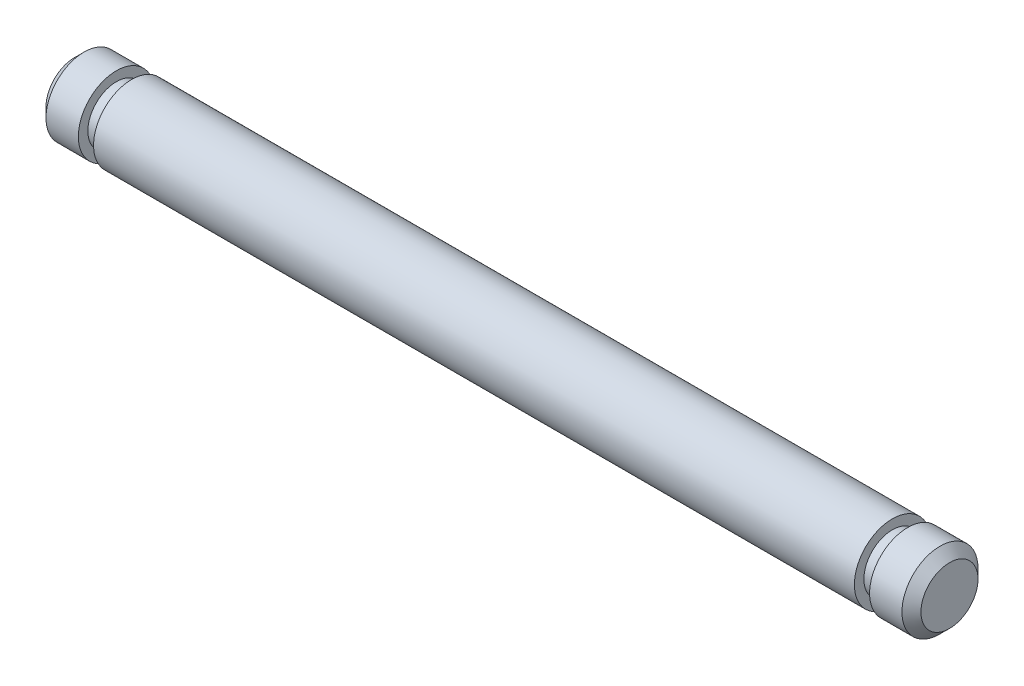
SolidWorks part; units mm, degrees
material "Chrome Stainless Steel"
ref_plane "Front Plane" through (0, 0, 0) normal (0, 0, 1) x (1, 0, 0)
ref_plane "Top Plane" through (0, 0, 0) normal (0, 1, 0) x (1, 0, 0)
ref_plane "Right Plane" through (0, 0, 0) normal (1, 0, 0) x (0, 0, -1)
sketch "Sketch1" plane through (0, 0, 0) normal (1, 0, 0) x (0, 0, -1)
  circle A0 centre (0, 0) radius 2
  dimension "D1" = 4
extrude "Boss-Extrude1" add sketch "Sketch1" along normal mid plane 40
sketch "Sketch2" plane through (20, 0, 0) normal (1, 0, 0) x (0, 0, -1)
  circle A0 centre (0, 0) radius 1.5
  dimension "D1" = 3
extrude "Boss-Extrude2" add sketch "Sketch2" along normal blind 0.8
sketch "Sketch3" plane through (20.8, 0, 0) normal (1, 0, 0) x (0, 0, -1)
  circle A0 centre (0, 0) radius 2
  dimension "D1" = 4
extrude "Boss-Extrude3" add sketch "Sketch3" along normal blind 2.2
mirror "Mirror1" about plane through (0, 0, 0) normal (1, 0, 0) of "Boss-Extrude3", "Boss-Extrude2"
chamfer "Chamfer1" distance 0.5 angle 45 2 edges at (-23, 0, -2) (23, 0, -2)
